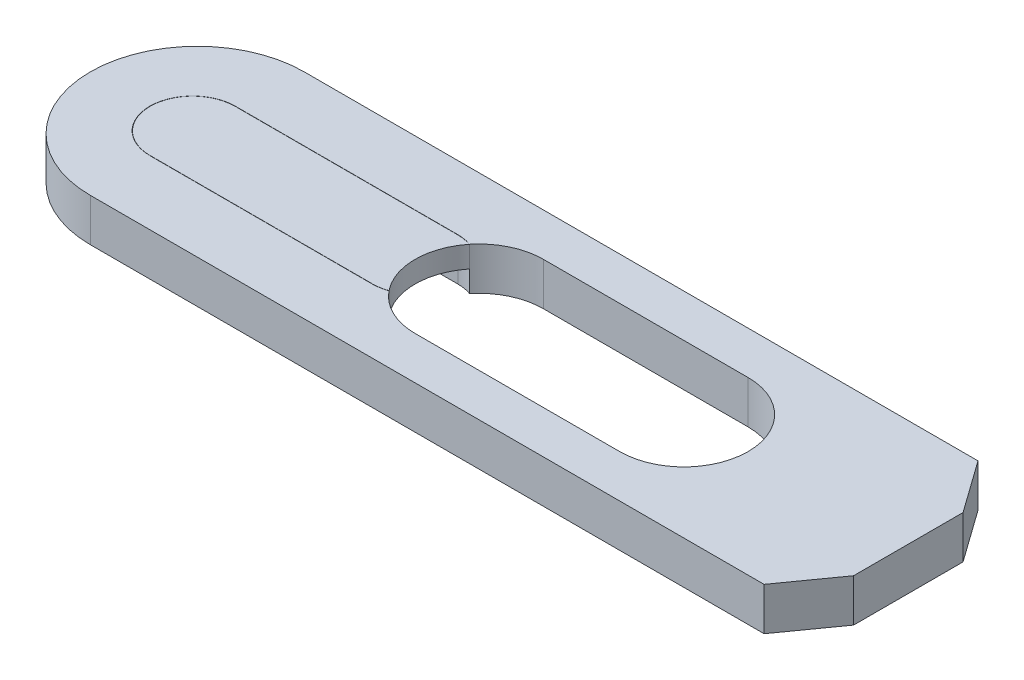
SolidWorks part; units mm, degrees
ref_plane "Front" through (0, 0, 0) normal (0, 0, 1) x (1, 0, 0)
ref_plane "Top" through (0, 0, 0) normal (0, 1, 0) x (1, 0, 0)
ref_plane "Right" through (0, 0, 0) normal (1, 0, 0) x (0, 0, -1)
sketch "Sketch1" plane through (0, 0, 0) normal (0, 1, 0) x (1, 0, 0)
  line L1 (40.005, -10.16) -> (-40.005, -10.16)
  line L3 (40.005, 15.24) -> (-40.005, 15.24)
  line L5 (0, 0) -> (-35.1571, 8.9288) construction
  line L6 (0, 0) -> (-35.1571, -8.9288) construction
  arc A0 (-40.005, 15.24) -> (-40.005, -10.16) centre (-40.005, 2.54) ccw
  arc A1 (40.005, -10.16) -> (40.005, 15.24) centre (40.005, 2.54) ccw
  point P0 (0, 0)
  dimension "D1" = 25.4
  dimension "D2" = 80.01
extrude "Boss-Extrude1" add sketch "Sketch1" along normal blind 5.08
sketch "Sketch2" plane through (0, 5.08, 0) normal (0, 1, 0) x (1, 0, 0)
  line L0 (-6.524, 2.54) -> (-52.705, 2.54) construction
  line L1 (-52.705, 2.54) -> (52.705, 2.54) construction
  line L2 (-6.524, 2.54) -> (17.7837, 2.54) construction
  line L3 (-6.524, 10.16) -> (17.7837, 10.16)
  line L4 (-6.524, -5.08) -> (17.7837, -5.08)
  line L5 (-40.5569, 2.54) -> (-14.144, 2.54) construction
  line L6 (-40.5569, 7.62) -> (-14.144, 7.62)
  line L7 (-40.5569, -2.54) -> (-14.144, -2.54)
  arc A0 (-40.005, 15.24) -> (-40.005, -10.16) centre (-40.005, 2.54) ccw construction
  arc A1 (40.005, -10.16) -> (40.005, 15.24) centre (40.005, 2.54) ccw construction
  arc A2 (-6.524, 10.16) -> (-12.4506, 7.3295) centre (-6.524, 2.54) ccw
  arc A3 (17.7837, -5.08) -> (17.7837, 10.16) centre (17.7837, 2.54) ccw
  arc A4 (-40.5569, 7.62) -> (-40.5569, -2.54) centre (-40.5569, 2.54) ccw
  arc A5 (-14.144, -2.54) -> (-12.4506, -2.2495) centre (-14.144, 2.54) ccw
  arc A6 (-12.4506, -2.2495) -> (-6.524, -5.08) centre (-6.524, 2.54) ccw
  arc A7 (-12.4506, 7.3295) -> (-14.144, 7.62) centre (-14.144, 2.54) ccw
  point P6 (11.1642, 2.54)
  point P16 (-27.3504, 2.54)
  dimension "D1" = 7.62
  dimension "D2" = 5.08
extrude "Cut-Extrude1" cut sketch "Sketch2" against normal through all
sketch "Sketch3" plane through (0, 5.08, 0) normal (0, 1, 0) x (1, 0, 0)
  line L0 (-40.5569, 2.54) -> (-14.144, 2.54) construction
  line L1 (-40.5569, 7.5931) -> (-14.144, 7.5931)
  line L2 (-40.5569, -2.5131) -> (-14.144, -2.5131)
  line L4 (-14.144, 7.62) -> (-40.5569, 7.62)
  line L5 (17.7837, 10.16) -> (-6.524, 10.16)
  line L6 (-6.524, -5.08) -> (17.7837, -5.08)
  line L7 (-40.5569, -2.54) -> (-14.144, -2.54)
  line L8 (-14.144, 7.62) -> (-40.5569, 7.62)
  line L9 (17.7837, 10.16) -> (-6.524, 10.16)
  line L10 (-6.524, -5.08) -> (17.7837, -5.08)
  line L11 (-40.5569, -2.54) -> (-14.144, -2.54)
  arc A0 (-12.4506, 7.3295) -> (-12.4685, 7.3073) centre (-6.524, 2.54) ccw
  arc A1 (-40.5569, 7.5931) -> (-40.5569, -2.5131) centre (-40.5569, 2.54) ccw
  arc A2 (-14.144, -2.5131) -> (-12.4685, -2.2273) centre (-14.144, 2.54) ccw
  arc A3 (-6.524, -5.08) -> (-6.524, 10.16) centre (-6.524, 2.54) ccw
  arc A4 (-12.4685, -2.2273) -> (-12.4506, -2.2495) centre (-6.524, 2.54) ccw
  circle A5 centre (-6.524, 2.54) radius 7.62
  arc A6 (-12.4506, 7.3295) -> (-14.144, 7.62) centre (-14.144, 2.54) ccw
  arc A7 (-6.524, 10.16) -> (-12.4506, 7.3295) centre (-6.524, 2.54) ccw
  arc A8 (17.7837, -5.08) -> (17.7837, 10.16) centre (17.7837, 2.54) ccw
  arc A9 (-12.4506, -2.2495) -> (-6.524, -5.08) centre (-6.524, 2.54) ccw
  arc A10 (-14.144, -2.54) -> (-12.4506, -2.2495) centre (-14.144, 2.54) ccw
  arc A11 (-40.5569, 7.62) -> (-40.5569, -2.54) centre (-40.5569, 2.54) ccw
  arc A12 (-12.4506, 7.3295) -> (-14.144, 7.62) centre (-14.144, 2.54) ccw
  arc A14 (17.7837, -5.08) -> (17.7837, 10.16) centre (17.7837, 2.54) ccw
  arc A16 (-14.144, -2.54) -> (-12.4506, -2.2495) centre (-14.144, 2.54) ccw
  arc A17 (-40.5569, 7.62) -> (-40.5569, -2.54) centre (-40.5569, 2.54) ccw
  arc A18 (-12.4685, 7.3073) -> (-14.144, 7.5931) centre (-14.144, 2.54) ccw
  point P4 (-27.3504, 2.54)
  dimension "D1" = 0
extrude "Boss-Extrude2" add sketch "Sketch3" against normal blind 2.54 separate body
sketch "Sketch4" plane through (0, 5.08, 0) normal (0, 1, 0) x (1, 0, 0)
  line L0 (52.705, 2.54) -> (-52.705, 2.54) construction
  line L1 (40.005, 15.24) -> (44.4313, 9.0374)
  line L2 (40.005, 15.24) -> (-40.005, 15.24) construction
  line L3 (44.4313, 9.0374) -> (44.4313, -3.9574)
  line L4 (44.4313, -3.9574) -> (40.005, -10.16)
  line L5 (-40.005, -10.16) -> (40.005, -10.16) construction
  line L6 (40.005, 15.24) -> (70.3146, 15.24)
  line L7 (70.3146, 15.24) -> (70.3146, -12.2275)
  line L8 (70.3146, -12.2275) -> (40.005, -12.2275)
  line L9 (40.005, -12.2275) -> (40.005, -10.16)
  arc A0 (40.005, -10.16) -> (40.005, 15.24) centre (40.005, 2.54) ccw construction
  arc A1 (-40.005, 15.24) -> (-40.005, -10.16) centre (-40.005, 2.54) ccw construction
  dimension "D1" = 7.62
  dimension "D2" = 7.62
  dimension "D3" = 12.9948
extrude "Cut-Extrude2" cut sketch "Sketch4" against normal through all
